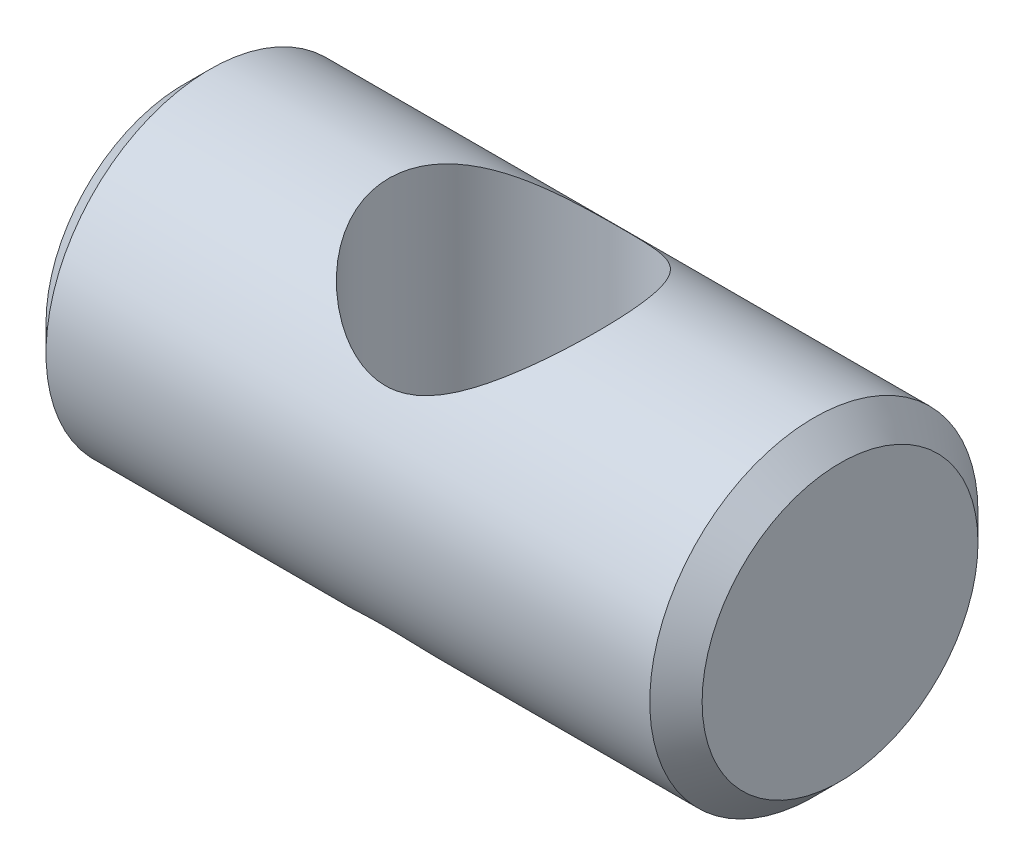
SolidWorks part; units mm, degrees
ref_plane "Front Plane" through (0, 0, 0) normal (0, 0, 1) x (1, 0, 0)
ref_plane "Top Plane" through (0, 0, 0) normal (0, 1, 0) x (1, 0, 0)
ref_plane "Right Plane" through (0, 0, 0) normal (1, 0, 0) x (0, 0, -1)
sketch "Sketch1" plane through (0, 0, 0) normal (1, 0, 0) x (0, 0, -1)
  circle A0 centre (0, 0) radius 4.765
  dimension "D1" = 9.53
extrude "Boss-Extrude1" add sketch "Sketch1" along normal mid plane 19.05
chamfer "Chamfer1" distance 0.76 angle 45 2 edges at (-9.525, 0, -4.765) (9.525, 0, -4.765)
sketch "Sketch2" plane through (0, 0, 0) normal (0, 1, 0) x (1, 0, 0)
  circle A0 centre (0, -0.25) radius 3.43
  point P2 (0, 0)
  dimension "D1" = 6.86
  dimension "D2" = 0.25
extrude "Cut-Extrude1" cut sketch "Sketch2" against normal through all both and the other way through all
